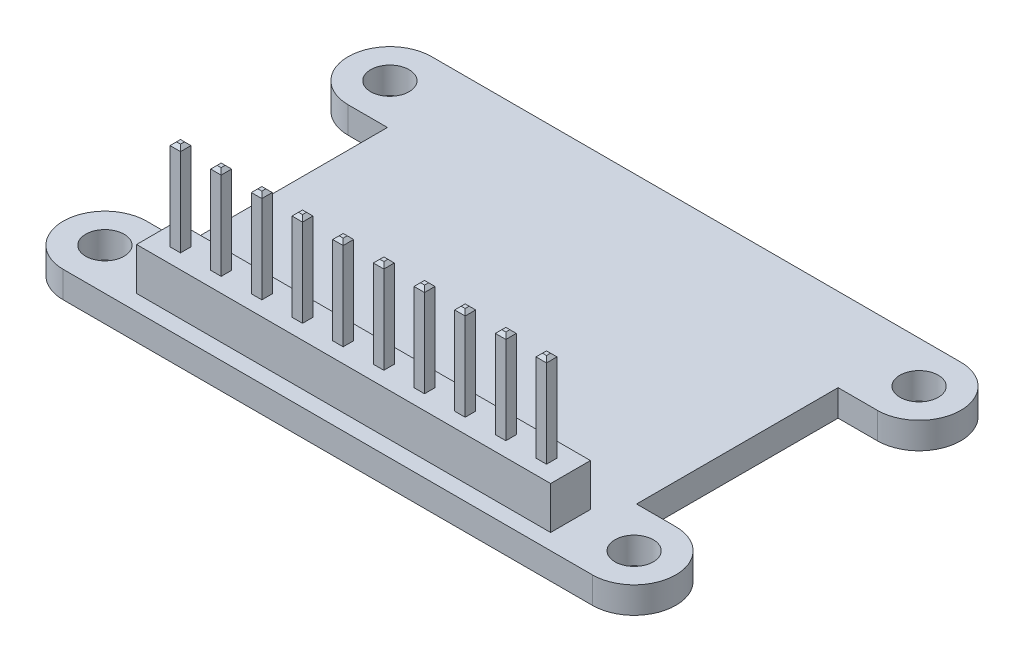
SolidWorks part; units mm, degrees
material "ABS"
ref_plane "Front" through (0, 0, 0) normal (0, 0, 1) x (1, 0, 0)
ref_plane "Top" through (0, 0, 0) normal (0, 1, 0) x (1, 0, 0)
ref_plane "Right" through (0, 0, 0) normal (1, 0, 0) x (0, 0, -1)
sketch "Sketch1" plane through (0, 0, 0) normal (0, 1, 0) x (1, 0, 0)
  line L0 (-16.4125, 0) -> (16.4125, 0)
  line L1 (16.4125, 5.175) -> (13.975, 5.175)
  line L2 (13.975, 5.175) -> (13.975, 17.675)
  line L3 (13.975, 17.675) -> (16.4125, 17.675)
  line L4 (16.4125, 22.85) -> (-16.4125, 22.85)
  line L5 (-16.4125, 17.675) -> (-13.975, 17.675)
  line L6 (-13.975, 17.675) -> (-13.975, 5.175)
  line L7 (-13.975, 5.175) -> (-16.4125, 5.175)
  arc A0 (16.4125, 0) -> (16.4125, 5.175) centre (16.4125, 2.5875) ccw
  arc A1 (16.4125, 17.675) -> (16.4125, 22.85) centre (16.4125, 20.2625) ccw
  arc A2 (-16.4125, 22.85) -> (-16.4125, 17.675) centre (-16.4125, 20.2625) ccw
  arc A3 (-16.4125, 5.175) -> (-16.4125, 0) centre (-16.4125, 2.5875) ccw
  circle A4 centre (16.4125, 20.2625) radius 1.19
  circle A5 centre (-16.4125, 20.2625) radius 1.19
  circle A6 centre (-16.4125, 2.5875) radius 1.19
  circle A7 centre (16.4125, 2.5875) radius 1.19
  point P21 (0, 0)
  point P23 (19, 20.2625)
  point P24 (-19, 20.2625)
  dimension "D3" = 38
  dimension "D5" = 2.38
  dimension "D1" = 27.95
  dimension "D2" = 22.85
  dimension "D4" = 12.5
extrude "Boss-Extrude1" add sketch "Sketch1" along normal blind 1.64
sketch "Sketch2" plane through (0, 1.64, 0) normal (0, 1, 0) x (1, 0, 0)
  line L0 (-16.4125, 0) -> (16.4125, 0) construction
  line L1 (12.84, 0.98) -> (-12.84, 0.98)
  line L2 (12.84, 0.98) -> (12.84, 3.45)
  line L3 (12.84, 3.45) -> (-12.84, 3.45)
  line L4 (-12.84, 0.98) -> (-12.84, 3.45)
  point P4 (0, 0.98)
  point P7 (0, 0)
  dimension "D1" = 25.68
  dimension "D2" = 2.47
  dimension "D3" = 3.45
extrude "Boss-Extrude2" add sketch "Sketch2" along normal blind 2.63
sketch "Sketch3" plane through (0, 4.27, 0) normal (0, 1, 0) x (1, 0, 0)
  line L0 (12.84, 0.98) -> (12.84, 3.45) construction
  line L1 (11.675, 2.54) -> (11.025, 2.54)
  line L2 (11.675, 2.54) -> (11.675, 1.89)
  line L3 (11.675, 1.89) -> (11.025, 1.89)
  line L4 (11.025, 2.54) -> (11.025, 1.89)
  line L5 (9.1528, 2.54) -> (9.1528, 1.89)
  line L6 (9.1528, 2.54) -> (8.5028, 2.54)
  line L7 (8.5028, 2.54) -> (8.5028, 1.89)
  line L8 (9.1528, 1.89) -> (8.5028, 1.89)
  line L9 (6.6306, 2.54) -> (6.6306, 1.89)
  line L10 (6.6306, 2.54) -> (5.9806, 2.54)
  line L11 (5.9806, 2.54) -> (5.9806, 1.89)
  line L12 (6.6306, 1.89) -> (5.9806, 1.89)
  line L13 (4.1083, 2.54) -> (4.1083, 1.89)
  line L14 (4.1083, 2.54) -> (3.4583, 2.54)
  line L15 (3.4583, 2.54) -> (3.4583, 1.89)
  line L16 (4.1083, 1.89) -> (3.4583, 1.89)
  line L17 (1.5861, 2.54) -> (1.5861, 1.89)
  line L18 (1.5861, 2.54) -> (0.9361, 2.54)
  line L19 (0.9361, 2.54) -> (0.9361, 1.89)
  line L20 (1.5861, 1.89) -> (0.9361, 1.89)
  line L21 (-0.9361, 2.54) -> (-0.9361, 1.89)
  line L22 (-0.9361, 2.54) -> (-1.5861, 2.54)
  line L23 (-1.5861, 2.54) -> (-1.5861, 1.89)
  line L24 (-0.9361, 1.89) -> (-1.5861, 1.89)
  line L25 (-3.4583, 2.54) -> (-3.4583, 1.89)
  line L26 (-3.4583, 2.54) -> (-4.1083, 2.54)
  line L27 (-4.1083, 2.54) -> (-4.1083, 1.89)
  line L28 (-3.4583, 1.89) -> (-4.1083, 1.89)
  line L29 (-5.9806, 2.54) -> (-5.9806, 1.89)
  line L30 (-5.9806, 2.54) -> (-6.6306, 2.54)
  line L31 (-6.6306, 2.54) -> (-6.6306, 1.89)
  line L32 (-5.9806, 1.89) -> (-6.6306, 1.89)
  line L33 (-8.5028, 2.54) -> (-8.5028, 1.89)
  line L34 (-8.5028, 2.54) -> (-9.1528, 2.54)
  line L35 (-9.1528, 2.54) -> (-9.1528, 1.89)
  line L36 (-8.5028, 1.89) -> (-9.1528, 1.89)
  line L37 (-11.025, 2.54) -> (-11.025, 1.89)
  line L38 (-11.025, 2.54) -> (-11.675, 2.54)
  line L39 (-11.675, 2.54) -> (-11.675, 1.89)
  line L40 (-11.025, 1.89) -> (-11.675, 1.89)
  line L41 (0.9361, 2.215) -> (-0.9361, 2.215) construction
  line L42 (-12.84, 0.98) -> (12.84, 0.98) construction
  point P4 (11.675, 2.215)
  point P7 (12.84, 2.215)
  point P48 (0, 0.98)
  point P49 (0, 2.215)
  dimension "D2" = 0.65
  dimension "D3" = 23.35
  dimension "D1" = 10
extrude "Boss-Extrude3" add sketch "Sketch3" along normal blind 5.64
chamfer "Chamfer1" distance 0.2 angle 45 40 edges at (-11.025, 9.91, -2.215) (-11.35, 9.91, -1.89) (-11.675, 9.91, -2.215) (-11.35, 9.91, -2.54) (-5.9806, 9.91, -2.215) (-6.3056, 9.91, -1.89) (-6.6306, 9.91, -2.215) (-6.3056, 9.91, -2.54) (-8.5028, 9.91, -2.215) (-8.8278, 9.91, -1.89) (-9.1528, 9.91, -2.215) (-8.8278, 9.91, -2.54) (-3.4583, 9.91, -2.215) (-3.7833, 9.91, -1.89) (-4.1083, 9.91, -2.215) (-3.7833, 9.91, -2.54) (-0.9361, 9.91, -2.215) (-1.2611, 9.91, -1.89) (-1.5861, 9.91, -2.215) (-1.2611, 9.91, -2.54) (1.5861, 9.91, -2.215) (1.2611, 9.91, -1.89) (0.9361, 9.91, -2.215) (1.2611, 9.91, -2.54) (4.1083, 9.91, -2.215) (3.7833, 9.91, -1.89) (3.4583, 9.91, -2.215) (3.7833, 9.91, -2.54) (6.6306, 9.91, -2.215) (6.3056, 9.91, -1.89) (5.9806, 9.91, -2.215) (6.3056, 9.91, -2.54) (9.1528, 9.91, -2.215) (8.8278, 9.91, -1.89) (8.5028, 9.91, -2.215) (8.8278, 9.91, -2.54) (11.35, 9.91, -1.89) (11.025, 9.91, -2.215) (11.35, 9.91, -2.54) (11.675, 9.91, -2.215)
